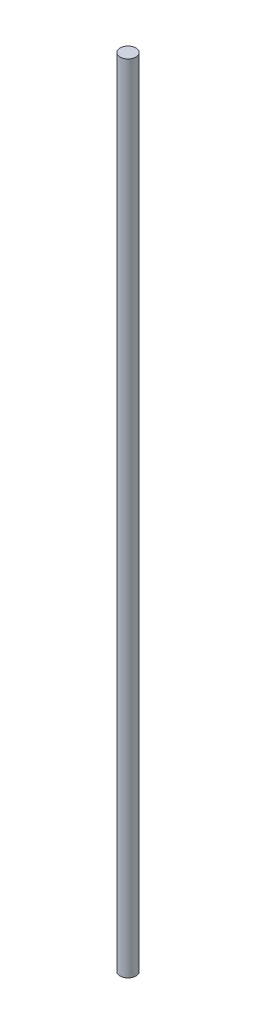
SolidWorks part; units mm, degrees
material "1060 Alloy"
ref_plane "Front Plane" through (0, 0, 0) normal (0, 0, 1) x (1, 0, 0)
ref_plane "Top Plane" through (0, 0, 0) normal (0, 1, 0) x (1, 0, 0)
ref_plane "Right Plane" through (0, 0, 0) normal (1, 0, 0) x (0, 0, -1)
sketch "Sketch1" plane through (0, 0, 0) normal (0, 1, 0) x (1, 0, 0)
  circle A0 centre (0, 0) radius 2.5
extrude "Boss-Extrude1" add sketch "Sketch1" along normal blind 250
